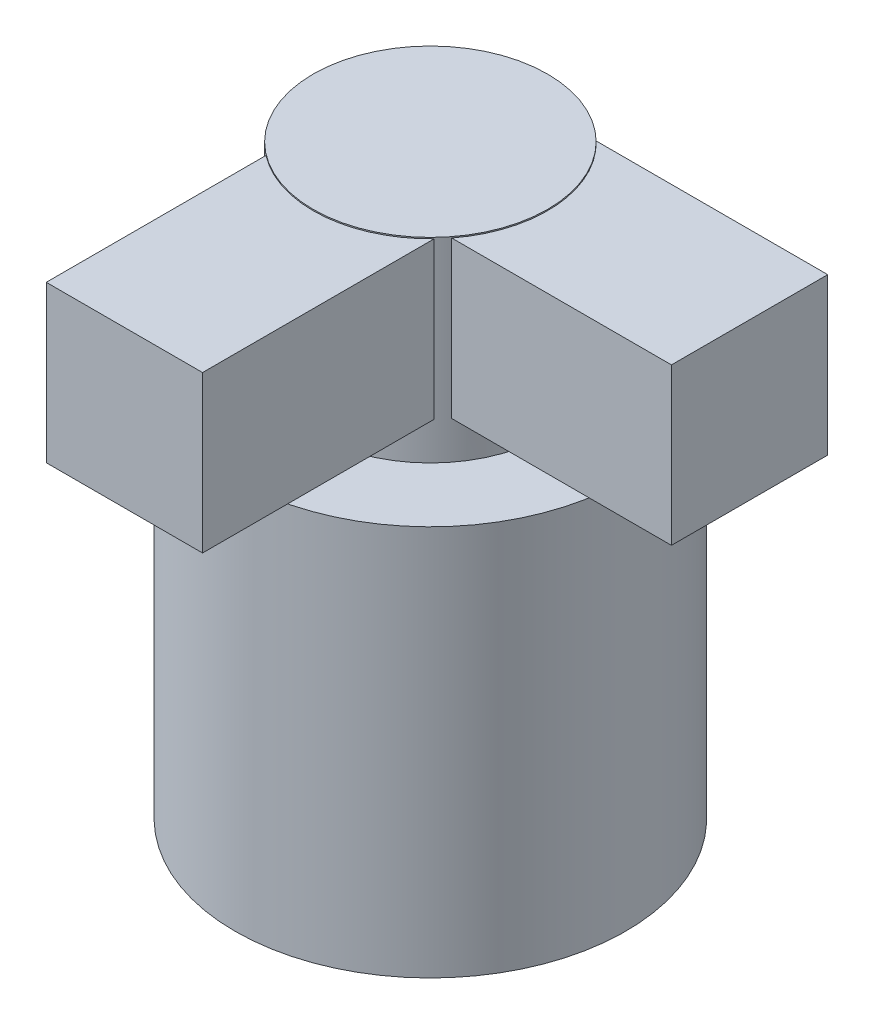
SolidWorks part; units mm, degrees
ref_plane "Front Plane" through (0, 0, 0) normal (0, 0, 1) x (1, 0, 0)
ref_plane "Top Plane" through (0, 0, 0) normal (0, 1, 0) x (1, 0, 0)
ref_plane "Right Plane" through (0, 0, 0) normal (1, 0, 0) x (0, 0, -1)
sketch "Sketch1" plane through (0, 0, 0) normal (0, 1, 0) x (1, 0, 0)
  circle A0 centre (0, 0) radius 5
  dimension "D1" = 10
extrude "Boss-Extrude1" add sketch "Sketch1" along normal blind 10
sketch "Sketch2" plane through (0, 10, 0) normal (0, 1, 0) x (1, 0, 0)
  circle A0 centre (0, 0) radius 3
  dimension "D1" = 6
extrude "Boss-Extrude2" add sketch "Sketch2" along normal blind 5
sketch "Sketch3" plane through (0, 0, 0) normal (0, -1, 0) x (1, 0, 0)
  circle A0 centre (0, 0) radius 3
  dimension "D1" = 6
extrude "Cut-Extrude1" cut sketch "Sketch3" against normal blind 5
sketch "Sketch4" plane through (0, 0, 0) normal (0, 0, 1) x (1, 0, 0)
  line L0 (3, 15) -> (-3, 15) construction
  line L1 (2.1697, 10.9691) -> (-1.8303, 10.9691)
  line L2 (2.1697, 10.9691) -> (2.1697, 14.9691)
  line L3 (2.1697, 14.9691) -> (-1.8303, 14.9691)
  line L4 (-1.8303, 10.9691) -> (-1.8303, 14.9691)
  line L5 (2.1697, 10.9691) -> (-1.8303, 14.9691) construction
  line L6 (2.1697, 14.9691) -> (-1.8303, 10.9691) construction
  point P0 (0.1697, 12.9691)
  dimension "D1" = 4
  dimension "D2" = 4
extrude "Boss-Extrude3" add sketch "Sketch4" along normal blind 8
pattern_circular "CirPattern1" count 2 over 90 about axis through (0, 0, 0) along (0, 1, 0) of "Boss-Extrude3"
